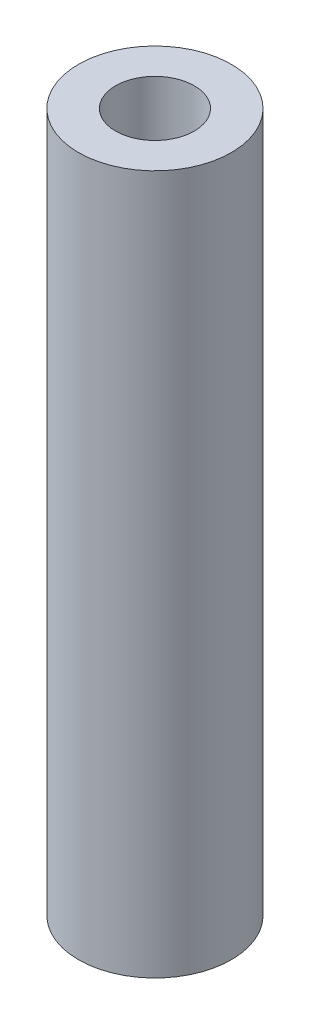
SolidWorks part; units mm, degrees
ref_plane "前视基准面" through (0, 0, 0) normal (0, 0, 1) x (1, 0, 0)
ref_plane "上视基准面" through (0, 0, 0) normal (0, 1, 0) x (1, 0, 0)
ref_plane "右视基准面" through (0, 0, 0) normal (1, 0, 0) x (0, 0, -1)
sketch "草图1" plane through (0, 0, 0) normal (0, 1, 0) x (1, 0, 0)
  circle A0 centre (0, 0) radius 1.75
  circle A1 centre (0, 0) radius 0.9
  dimension "D1" = 1.8
  dimension "D2" = 3.5
extrude "凸台-拉伸1" add sketch "草图1" along normal blind 16
equation "\"m\"= 2"
